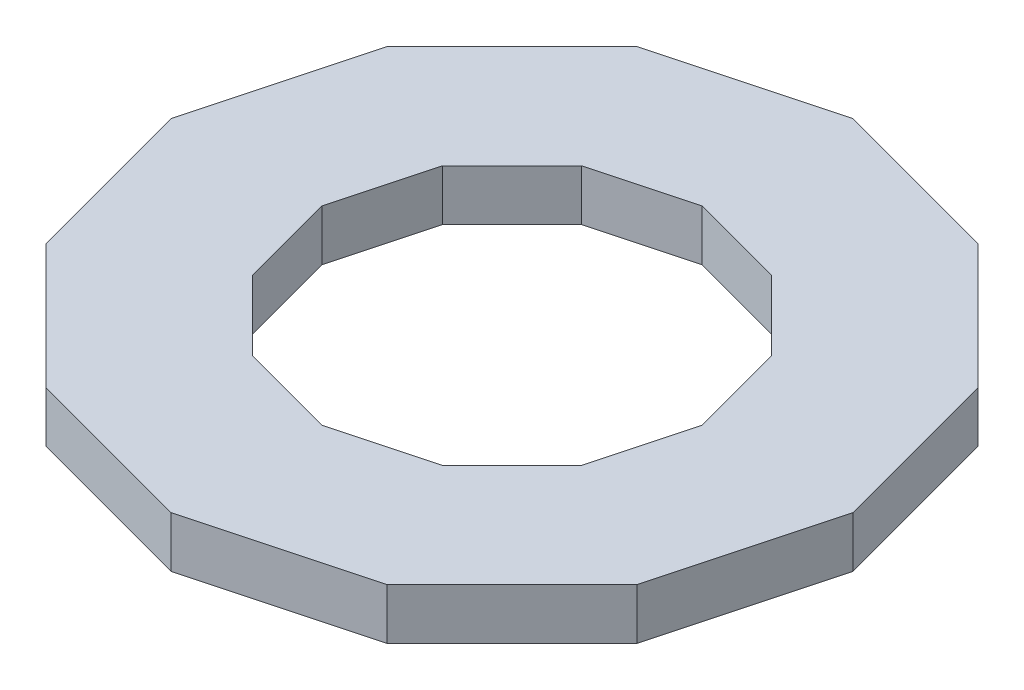
SolidWorks part; units mm, degrees
ref_plane "Front Plane" through (0, 0, 0) normal (0, 0, 1) x (1, 0, 0)
ref_plane "Top Plane" through (0, 0, 0) normal (0, 1, 0) x (1, 0, 0)
ref_plane "Right Plane" through (0, 0, 0) normal (1, 0, 0) x (0, 0, -1)
sketch "Sketch2" plane through (0, 0, 0) normal (0, 1, 0) x (1, 0, 0)
  line L0 (0, 0) -> (-71.0431, 0) construction
  line L1 (-127.5795, 0) -> (-110.4871, -63.7897)
  line L2 (-110.4871, -63.7897) -> (-63.7897, -110.4871)
  line L3 (-63.7897, -110.4871) -> (0, -127.5795)
  line L4 (0, -127.5795) -> (63.7897, -110.4871)
  line L5 (63.7897, -110.4871) -> (110.4871, -63.7897)
  line L6 (110.4871, -63.7897) -> (127.5795, 0)
  line L7 (127.5795, 0) -> (110.4871, 63.7897)
  line L8 (110.4871, 63.7897) -> (63.7897, 110.4871)
  line L9 (63.7897, 110.4871) -> (0, 127.5795)
  line L10 (0, 127.5795) -> (-63.7897, 110.4871)
  line L11 (-63.7897, 110.4871) -> (-110.4871, 63.7897)
  line L12 (-110.4871, 63.7897) -> (-127.5795, 0)
  line L13 (-71.0431, 0) -> (-61.5251, -35.5215)
  line L14 (-61.5251, -35.5215) -> (-35.5215, -61.5251)
  line L15 (-35.5215, -61.5251) -> (0, -71.0431)
  line L16 (0, -71.0431) -> (35.5215, -61.5251)
  line L17 (35.5215, -61.5251) -> (61.5251, -35.5215)
  line L18 (61.5251, -35.5215) -> (71.0431, 0)
  line L19 (71.0431, 0) -> (61.5251, 35.5215)
  line L20 (61.5251, 35.5215) -> (35.5215, 61.5251)
  line L21 (35.5215, 61.5251) -> (0, 71.0431)
  line L22 (0, 71.0431) -> (-35.5215, 61.5251)
  line L23 (-35.5215, 61.5251) -> (-61.5251, 35.5215)
  line L24 (-61.5251, 35.5215) -> (-71.0431, 0)
  line L25 (-127.5795, 0) -> (-71.0431, 0) construction
  line L26 (-71.0431, 0) -> (-71.7748, 0.6809) construction
  circle A0 centre (0, 0) radius 123.2323 construction
  circle A1 centre (0, 0) radius 68.6223 construction
  dimension "D1" = 66.04
  dimension "D2" = 54.61
extrude "Boss-Extrude2" add sketch "Sketch2" along normal blind 19.05
